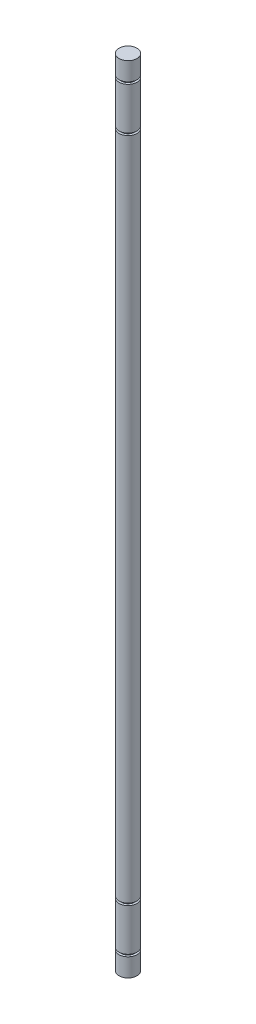
SolidWorks part; units mm, degrees
material "AISI 4130 Steel, annealed at 865C"
ref_plane "Front Plane" through (0, 0, 0) normal (0, 0, 1) x (1, 0, 0)
ref_plane "Top Plane" through (0, 0, 0) normal (0, 1, 0) x (1, 0, 0)
ref_plane "Right Plane" through (0, 0, 0) normal (1, 0, 0) x (0, 0, -1)
sketch "Sketch1" plane through (0, 0, 0) normal (0, 1, 0) x (1, 0, 0)
  circle A0 centre (0, 0) radius 1.5875
  dimension "D1" = 3.175
extrude "Boss-Extrude1" add sketch "Sketch1" along normal mid plane 140.1318
sketch "Sketch2" plane through (0, 0, 0) normal (0, 0, 1) x (1, 0, 0)
  line L1 (1.2065, 59.0042) -> (1.5875, 59.0042)
  line L2 (1.2065, 59.0042) -> (1.2065, 58.6232)
  line L3 (1.2065, 58.6232) -> (1.5875, 58.6232)
  line L4 (1.5875, 59.0042) -> (1.5875, 58.6232)
  line L5 (1.5875, -70.0659) -> (1.5875, 70.0659) construction
  line L6 (0, -58.6232) -> (0, 58.6232) construction
  line L7 (1.2065, -58.6232) -> (1.5875, -58.6232)
  line L8 (1.2065, -58.6232) -> (1.2065, -59.0042)
  line L9 (1.2065, -59.0042) -> (1.5875, -59.0042)
  line L10 (1.5875, -58.6232) -> (1.5875, -59.0042)
  line L11 (1.2065, 66.8274) -> (1.5875, 66.8274)
  line L12 (1.2065, 66.8274) -> (1.2065, 66.4464)
  line L13 (1.2065, 66.4464) -> (1.5875, 66.4464)
  line L14 (1.5875, 66.8274) -> (1.5875, 66.4464)
  line L15 (1.2065, -66.4464) -> (1.5875, -66.4464)
  line L16 (1.2065, -66.4464) -> (1.2065, -66.8274)
  line L17 (1.2065, -66.8274) -> (1.5875, -66.8274)
  line L18 (1.5875, -66.4464) -> (1.5875, -66.8274)
  point P20 (1.5875, -58.8137)
  point P21 (1.5875, -66.6369)
  point P22 (1.5875, 66.6369)
  point P23 (1.5875, 58.8137)
  point P26 (0, 0)
  dimension "D1" = 0.381
  dimension "D2" = 7.8232
  dimension "D3" = 7.8232
  dimension "D4" = 117.6274
  dimension "D5" = 1.2065
  dimension "D6" = 117.2464
revolve "Cut-Revolve1" cut sketch "Sketch2" angle 360 about L6
